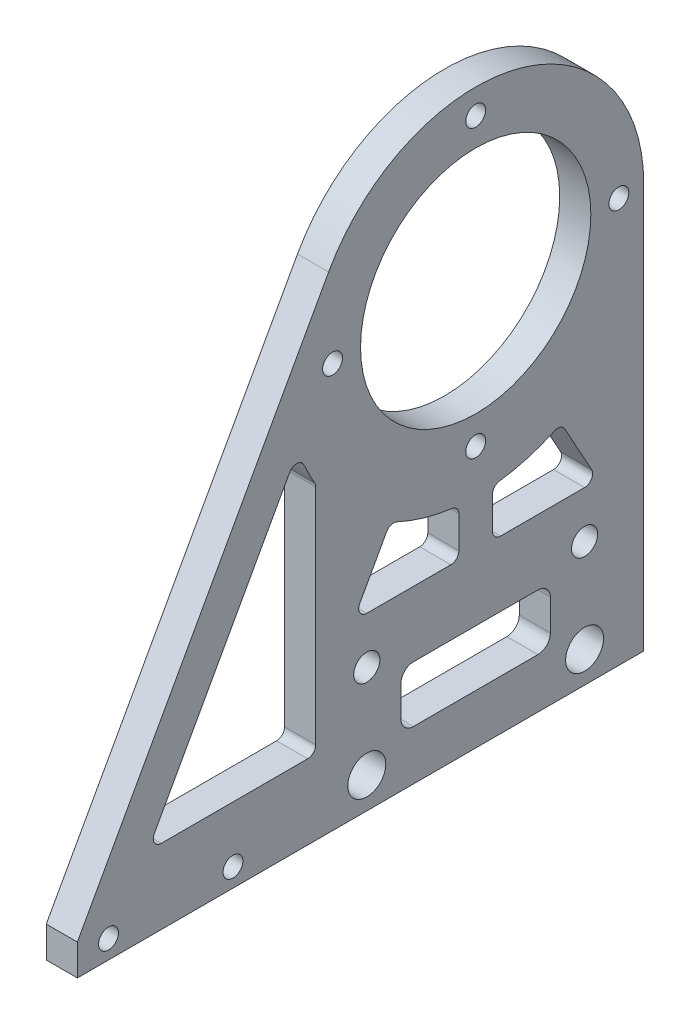
SolidWorks part; units mm, degrees
material "环氧树脂FR-4"
ref_plane "前视基准面" through (0, 0, 0) normal (0, 0, 1) x (1, 0, 0)
ref_plane "上视基准面" through (0, 0, 0) normal (0, 1, 0) x (1, 0, 0)
ref_plane "右视基准面" through (0, 0, 0) normal (1, 0, 0) x (0, 0, -1)
sketch "草图1" plane through (0, 0, 0) normal (1, 0, 0) x (0, 0, -1)
  circle A0 centre (0, 0) radius 18.5
  circle A1 centre (0, 0) radius 27
  dimension "D1" = 37
  dimension "D2" = 54
extrude "凸台-拉伸1" add sketch "草图1" along normal blind 5
sketch "草图2" plane through (5, 0, 0) normal (1, 0, 0) x (0, 0, -1)
  line L0 (0, 23) -> (0, 0) construction
  line L1 (0, 0) -> (0, 23) construction
  circle A0 centre (23, 0) radius 1.6
  circle A5 centre (0, -23) radius 1.6
  circle A6 centre (0, 23) radius 1.6
  circle A7 centre (-23, 0) radius 1.6
  dimension "D3" = 4
  dimension "D2" = 3.2
  dimension "D1" = 23
extrude "切除-拉伸1" cut sketch "草图2" against normal blind 10
sketch "草图3" plane through (0, 0, 0) normal (-1, 0, 0) x (0, 0, 1)
  line L0 (-27, 0) -> (-27, -200)
  line L2 (-27, -200) -> (64, -200)
  line L5 (23.6324, 13.0579) -> (64, -60)
  line L6 (64, -60) -> (64, -200)
  circle A0 centre (0, 0) radius 27 construction
  circle A1 centre (0, 0) radius 27 construction
  arc A3 (-27, 0) -> (27, 0) centre (0, 0) ccw
  dimension "D1" = 64
  dimension "D2" = 200
  dimension "D3" = 60
extrude "凸台-拉伸2" add sketch "草图3" against normal blind 5
sketch "草图4" plane through (0, 0, 0) normal (-1, 0, 0) x (0, 0, 1)
  line L0 (-9, -195) -> (51, -195) construction
  line L1 (-27, -200) -> (64, -200) construction
  circle A0 centre (51, -195) radius 2.6
  circle A1 centre (-9, -195) radius 2.6
  dimension "D3" = 5.2
  dimension "D1" = 13
  dimension "D2" = 60
  dimension "D4" = 5
extrude "切除-拉伸2" [suppressed] cut sketch "草图4" against normal through all
sketch "草图5" plane through (5, 0, 0) normal (1, 0, 0) x (0, 0, -1)
  line L1 (0, -105) -> (0, -76) construction
  circle A0 centre (0, -105) radius 25
  circle A1 centre (0, -76) radius 1.6
  circle A2 centre (25.1147, -119.5) radius 1.6
  circle A3 centre (-25.1147, -119.5) radius 1.6
  dimension "D1" = 50
  dimension "D6" = 3.2
  dimension "D2" = 105
  dimension "D3" = 0
  dimension "D5" = 29
  dimension "D4" = 3
extrude "切除-拉伸3" [suppressed] cut sketch "草图5" against normal through all
sketch "草图7" plane through (0, 0, 0) normal (1, 0, 0) x (0, 0, -1)
  line L0 (-64, -188) -> (-107, -188)
  line L1 (-64, -60) -> (-64, -200) construction
  line L2 (-107, -188) -> (-107, -53)
  line L3 (-107, -53) -> (-64, -53)
  line L4 (-64, -53) -> (-64, -188)
  line L5 (27, -200) -> (-64, -200) construction
  dimension "D1" = 12
  dimension "D2" = 135
  dimension "D3" = 43
extrude "凸台-拉伸3" [suppressed] add sketch "草图7" along normal through all separate body
sketch "草图9" plane through (5, 0, 0) normal (1, 0, 0) x (0, 0, -1)
  line L0 (-64, -65) -> (27, -65)
  line L1 (-64, -60) -> (-64, -200) construction
  line L3 (27, -65) -> (27, -200)
  line L4 (27, -200) -> (-64, -200)
  line L5 (-64, -200) -> (-64, -65)
  line L6 (27, 0) -> (27, -200) construction
  dimension "D1" = 135
extrude "切除-拉伸5" cut sketch "草图9" against normal through all
sketch "草图10" plane through (5, 0, 0) normal (1, 0, 0) x (0, 0, -1)
  line L0 (0, 0) -> (0, -65) construction
  line L1 (27, -65) -> (-64, -65) construction
  point P0 (0, 0)
sketch "草图13" plane through (5, 0, 0) normal (1, 0, 0) x (0, 0, -1)
  line L0 (0, 0) -> (0, -65) construction
  line L1 (27, -65) -> (-64, -65) construction
  line L3 (17.5, -60) -> (-17.5, -60) construction
  line L4 (17.5, -60) -> (17.5, -45) construction
  line L5 (17.5, -45) -> (-17.5, -45) construction
  line L6 (-17.5, -60) -> (-17.5, -45) construction
  line L7 (17.5, -60) -> (-17.5, -45) construction
  line L8 (17.5, -45) -> (-17.5, -60) construction
  circle A0 centre (-17.5, -45) radius 2.1
  circle A1 centre (-17.5, -60) radius 3.0525
  circle A2 centre (17.5, -60) radius 3.0525
  circle A3 centre (17.5, -45) radius 2.1
  point P5 (0, -52.5)
  dimension "D4" = 4.2
  dimension "D5" = 6.105
  dimension "D1" = 35
  dimension "D2" = 15
  dimension "D3" = 60
extrude "切除-拉伸6" cut sketch "草图13" against normal through all
sketch "草图14" plane through (0, 0, 0) normal (-1, 0, 0) x (0, 0, 1)
  line L0 (-27, -65) -> (64, -65) construction
  line L1 (59, -62) -> (39, -62) construction
  circle A0 centre (39, -62) radius 1.6
  circle A1 centre (59, -62) radius 1.6
  dimension "D1" = 39
  dimension "D3" = 3.2
  dimension "D4" = 20
  dimension "D2" = 3
extrude "切除-拉伸7" cut sketch "草图14" against normal through all
sketch "草图15" plane through (0, 0, 0) normal (-1, 0, 0) x (0, 0, 1)
  line L0 (-17.5, -45) -> (-17.5, -60) construction
  line L1 (17.5, -45) -> (17.5, -60) construction
  line L2 (-17.5, -52.5) -> (17.5, -52.5) construction
  line L4 (12, -57) -> (-12, -57)
  line L5 (12, -57) -> (12, -48)
  line L6 (12, -48) -> (-12, -48)
  line L7 (-12, -57) -> (-12, -48)
  line L8 (12, -57) -> (-12, -48) construction
  line L9 (12, -48) -> (-12, -57) construction
  point P10 (0, -52.5)
  dimension "D1" = 24
  dimension "D2" = 9
extrude "切除-拉伸8" cut sketch "草图15" against normal blind 10
fillet "圆角1" radius 2 4 edges at (2.5, -48, 12) (2.5, -48, -12) (2.5, -57, 12) (2.5, -57, -12)
sketch "草图16" plane through (5, 0, 0) normal (1, 0, 0) x (0, 0, -1)
  line L0 (-52.706, -53) -> (-28.5361, -9.257)
  line L1 (-52.706, -53) -> (-25.706, -53)
  line L2 (-25.706, -53) -> (-25.706, -15.4662)
  line L3 (-23.6324, 13.0579) -> (-64, -60) construction
  line L4 (27, -65) -> (-64, -65) construction
  circle A0 centre (0, 0) radius 30
  dimension "D1" = 60
  dimension "D2" = 12
  dimension "D3" = 6.5
  dimension "D4" = 27
extrude "切除-拉伸9" cut sketch "草图16" against normal through all contours A0 L0 L1 L2
fillet "圆角2" radius 1.3 4 edges at (2.5, -53, 25.706) (2.5, -53, 52.706) (2.5, -15.4662, 25.706) (2.5, -9.257, 28.5361)
sketch "草图17" plane through (5, 0, 0) normal (1, 0, 0) x (0, 0, -1)
  line L0 (0, 0) -> (0, -30) construction
  line L1 (-23.6324, 13.0579) -> (-64, -60) construction
  line L2 (-13.7207, -26.6785) -> (-19.7, -37.5)
  line L3 (-19.7, -37.5) -> (-2.7, -37.5)
  line L4 (-2.7, -37.5) -> (-2.7, -29.8783)
  line L5 (2.7, -37.5) -> (2.7, -29.8783)
  line L6 (19.7, -37.5) -> (2.7, -37.5)
  line L7 (13.7207, -26.6785) -> (19.7, -37.5)
  circle A0 centre (0, 0) radius 30
  dimension "D1" = 60
  dimension "D2" = 2.7
  dimension "D3" = 17
  dimension "D4" = 37.5
extrude "切除-拉伸10" cut sketch "草图17" against normal through all contours A0 L2 L3 L4 | A0 L5 L6 L7
fillet "圆角3" radius 1.3 8 edges at (2.5, -37.5, 19.7) (2.5, -37.5, -2.7) (2.5, -37.5, 2.7) (2.5, -37.5, -19.7) (2.5, -26.6785, -13.7207) (2.5, -29.8783, -2.7) (2.5, -29.8783, 2.7) (2.5, -26.6785, 13.7207)
